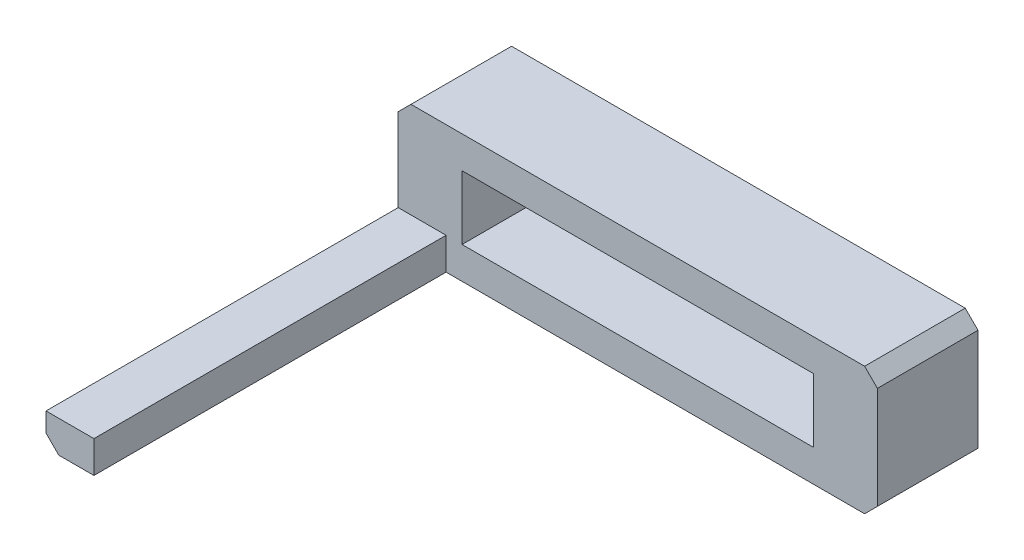
SolidWorks part; units mm, degrees
ref_plane "Front Plane" through (0, 0, 0) normal (0, 0, 1) x (1, 0, 0)
ref_plane "Top Plane" through (0, 0, 0) normal (0, 1, 0) x (1, 0, 0)
ref_plane "Right Plane" through (0, 0, 0) normal (1, 0, 0) x (0, 0, -1)
sketch "Sketch1" plane through (0, 0, 0) normal (0, 0, 1) x (1, 0, 0)
  line L1 (0, 0) -> (-95.25, 0)
  line L2 (0, 0) -> (0, 25.4)
  line L3 (0, 25.4) -> (-95.25, 25.4)
  line L4 (-95.25, 0) -> (-95.25, 25.4)
  line L5 (-12.7, 19.05) -> (-82.55, 19.05)
  line L6 (-12.7, 19.05) -> (-12.7, 6.35)
  line L7 (-12.7, 6.35) -> (-82.55, 6.35)
  line L8 (-82.55, 19.05) -> (-82.55, 6.35)
  point P9 (-47.625, 25.4)
  point P10 (-47.625, 6.35)
  point P11 (-12.7, 17.4903)
  dimension "D1" = 95.25
  dimension "D2" = 25.4
  dimension "D3" = 19.05
  dimension "D4" = 12.7
  dimension "D5" = 6.35
extrude "Boss-Extrude1" add sketch "Sketch1" along normal blind 20 contours L8 L3 L4 L1 L2 L6 L7
sketch "Sketch2" plane through (0, 0, 20) normal (0, 0, 1) x (1, 0, 0)
  line L1 (-95.25, 0) -> (-85.725, 0)
  line L2 (-95.25, 0) -> (-95.25, 6.35)
  line L3 (-95.25, 6.35) -> (-85.725, 6.35)
  line L4 (-85.725, 0) -> (-85.725, 6.35)
  dimension "D1" = 9.525
  dimension "D2" = 6.35
extrude "Boss-Extrude2" add sketch "Sketch2" along normal blind 70
chamfer "Chamfer1" distance 2.54 angle 45 4 edges at (0, 0, 10) (-95.25, 0, 45) (0, 25.4, 10) (-95.25, 25.4, 10)
